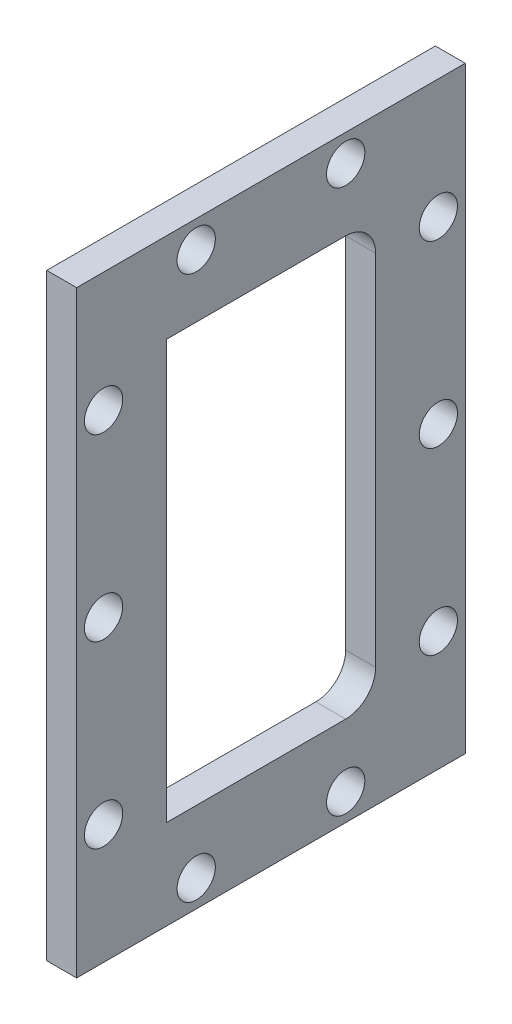
SolidWorks part; units mm, degrees
ref_plane "Front Plane" through (0, 0, 0) normal (0, 0, 1) x (1, 0, 0)
ref_plane "Top Plane" through (0, 0, 0) normal (0, 1, 0) x (1, 0, 0)
ref_plane "Right Plane" through (0, 0, 0) normal (1, 0, 0) x (0, 0, -1)
ref_plane "Plane1" through (0, 0, 0) normal (-1, 0, 0) x (0, -1, 0)
sketch "Sketch1" plane through (0, 0, 0) normal (-1, 0, 0) x (0, -1, 0)
  line L0 (0, 64.9999) -> (-99.9998, 64.9999)
  line L1 (-99.9998, 64.9999) -> (-99.9998, 0)
  line L2 (-99.9998, 0) -> (0, 0)
  line L3 (0, 0) -> (0, 64.9999)
extrude "Boss-Extrude1" add sketch "Sketch1" against normal blind 5
ref_plane "Plane2" through (0, 15, 0) normal (0, -1, 0) x (1, 0, 0)
sketch "Sketch2" plane through (0, 15, 0) normal (0, -1, 0) x (1, 0, 0)
  line L0 (0, 53.9999) -> (0, 15)
  line L1 (0, 15) -> (5, 15)
  line L2 (5, 15) -> (5, 49.9999)
  line L3 (5, 49.9999) -> (4, 49.9999)
  line L4 (4, 49.9999) -> (0, 53.9999)
extrude "Cut-Extrude1" cut sketch "Sketch2" against normal blind 69.9999
hole_wizard "Hole1" positions "Sketch4" profile "Sketch3" legacy
sketch "Sketch4" plane through (0, 0, 0) normal (-1, 0, 0) x (0, 0, 1)
  point P0 (60.4999, 20)
  point P1 (44.9999, 4.5)
  point P2 (20, 4.5)
  point P3 (4.5, 20)
  point P4 (4.5, 49.9999)
  point P5 (4.5, 79.9998)
  point P6 (20, 95.4998)
  point P7 (44.9999, 95.4998)
  point P8 (60.4999, 79.9998)
  point P9 (60.4999, 49.9999)
sketch "Sketch3" plane through (0, 20, 60.4999) normal (0, 1, 0) x (0, 0, 1)
  line L0 (0, 0) -> (0, 5)
  line L1 (0, 5) -> (3.2, 5)
  line L2 (3.2, 5) -> (3.2, 0)
  line L3 (3.2, 0) -> (0, 0)
  line L4 (0, 110) -> (0, -10) construction
  dimension "Diameter" = 6.4
  dimension "Depth" = 5
fillet "Fillet1" radius 5 2 edges at (2.5, 15, 15) (2.5, 84.9998, 15)
